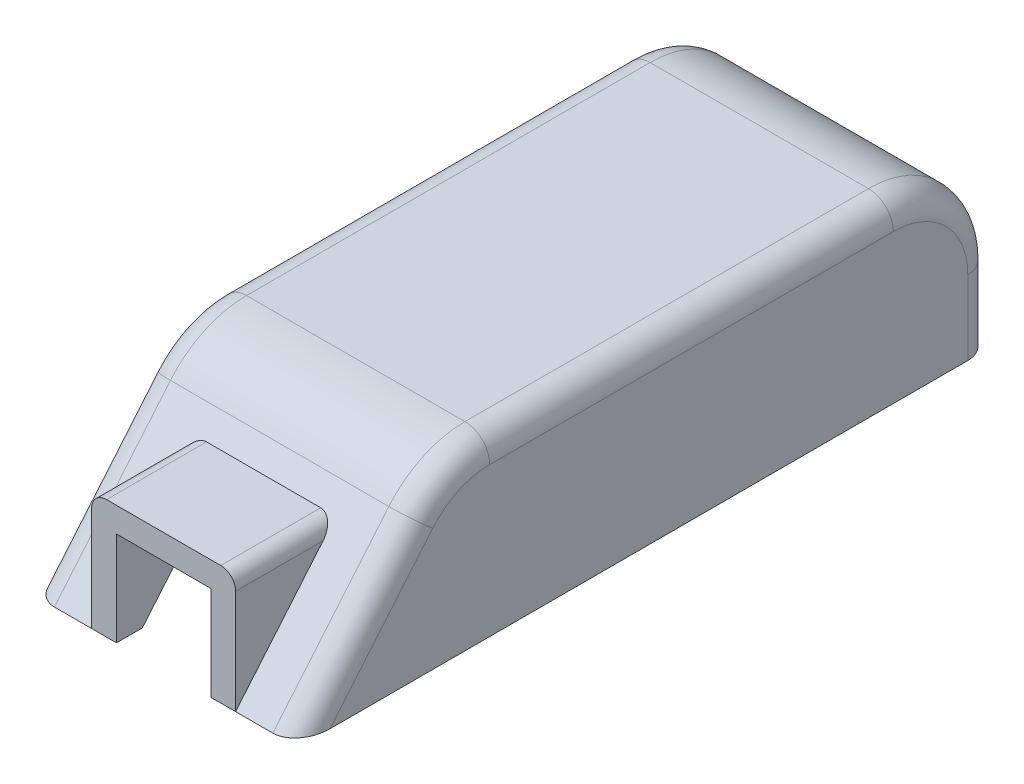
SolidWorks part; units mm, degrees
material "PE High Density"
ref_plane "Front Plane" through (0, 0, 0) normal (0, 0, 1) x (1, 0, 0)
ref_plane "Top Plane" through (0, 0, 0) normal (0, 1, 0) x (1, 0, 0)
ref_plane "Right Plane" through (0, 0, 0) normal (1, 0, 0) x (0, 0, -1)
sketch "Sketch1" plane through (0, 0, 0) normal (1, 0, 0) x (0, 0, -1)
  line L0 (0, 0) -> (29.3685, 35)
  line L1 (29.3685, 35) -> (140, 35)
  line L2 (140, 35) -> (140, 0)
  line L3 (140, 0) -> (0, 0)
  dimension "D1" = 140
  dimension "D2" = 35
  dimension "D3" = 50
extrude "Boss-Extrude1" add sketch "Sketch1" along normal blind 54
fillet "Fillet1" radius 20 2 edges at (27, 35, -140) (27, 35, -29.3685)
fillet "Fillet2" radius 5 10 edges at (0, 7.5, -140) (0, 29.1421, -134.1421) (0, 35, -79.3473) (0, 33.1262, -30.2423) (54, 7.5, -140) (54, 29.1421, -134.1421) (54, 35, -79.3473) (54, 33.1262, -30.2423) (0, 13.9279, -11.6869) (54, 13.9279, -11.6869)
shell "Shell1" thickness 4
sketch "Sketch2" plane through (0, 0, 0) normal (0, 0, 1) x (1, 0, 0)
  line L0 (49, 0) -> (5, 0) construction
  line L1 (12.5, 0) -> (41.5, 0)
  line L2 (12.5, 0) -> (12.5, 24)
  line L3 (12.5, 24) -> (41.5, 24)
  line L4 (41.5, 0) -> (41.5, 24)
  line L5 (27, 35) -> (27, 24) construction
  line L6 (5, 35) -> (49, 35) construction
  dimension "D1" = 29
  dimension "D2" = 24
extrude "Boss-Extrude2" add sketch "Sketch2" against normal up to surface up to face at (27, 13.9279, -11.6869)
sketch "Sketch3" plane through (0, 0, 0) normal (0, 0, 1) x (1, 0, 0)
  line L0 (12.5, 0) -> (41.5, 0) construction
  line L1 (17.5, 0) -> (36.5, 0)
  line L2 (17.5, 0) -> (17.5, 19)
  line L3 (17.5, 19) -> (36.5, 19)
  line L4 (36.5, 0) -> (36.5, 19)
  line L5 (12.5, 24) -> (12.5, 0) construction
  line L6 (41.5, 0) -> (41.5, 24) construction
  line L7 (41.5, 24) -> (12.5, 24) construction
  dimension "D1" = 5
  dimension "D2" = 5
  dimension "D3" = 5
extrude "Cut-Extrude1" cut sketch "Sketch3" against normal blind 54
fillet "Fillet3" radius 3 2 edges at (41.5, 24, -10.0692) (12.5, 24, -10.0692)
